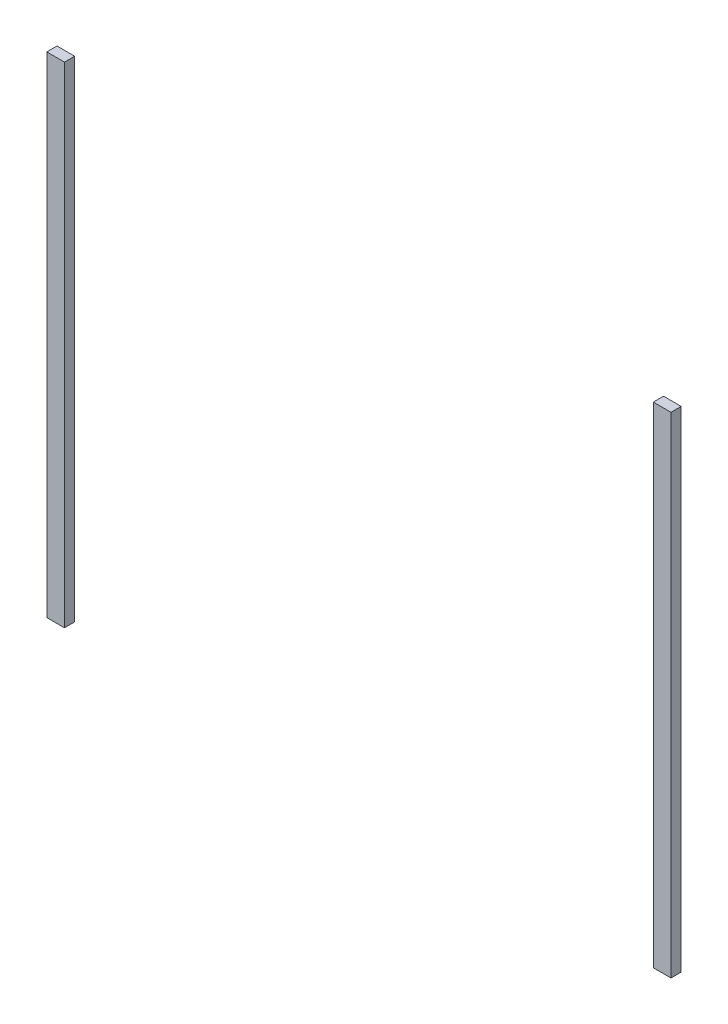
SolidWorks part; units mm, degrees
ref_plane "Front Plane" through (0, 0, 0) normal (0, 0, 1) x (1, 0, 0)
ref_plane "Top Plane" through (0, 0, 0) normal (0, 1, 0) x (1, 0, 0)
ref_plane "Right Plane" through (0, 0, 0) normal (1, 0, 0) x (0, 0, -1)
sketch "Sketch1" plane through (0, 609.6, 0) normal (0, 1, 0) x (1, 0, 0)
  line L4 (366.3353, -647.2114) -> (366.3353, -659.9114)
  line L5 (388.3323, -647.2114) -> (366.3353, -647.2114)
  line L6 (388.3323, -659.9114) -> (388.3323, -647.2114)
  line L7 (366.3353, -659.9114) -> (388.3323, -659.9114)
  line L8 (366.3353, -647.2114) -> (366.3353, -659.9114)
  line L9 (388.3323, -647.2114) -> (366.3353, -647.2114)
  line L10 (388.3323, -659.9114) -> (388.3323, -647.2114)
  line L11 (366.3353, -659.9114) -> (388.3323, -659.9114)
  line L12 (-366.3353, -659.9114) -> (-366.3353, -647.2114)
  line L13 (-366.3353, -647.2114) -> (-388.3323, -647.2114)
  line L14 (-388.3323, -647.2114) -> (-388.3323, -659.9114)
  line L15 (-388.3323, -659.9114) -> (-366.3353, -659.9114)
  line L16 (-366.3353, -659.9114) -> (-366.3353, -647.2114)
  line L17 (-366.3353, -647.2114) -> (-388.3323, -647.2114)
  line L18 (-388.3323, -647.2114) -> (-388.3323, -659.9114)
  line L19 (-388.3323, -659.9114) -> (-366.3353, -659.9114)
  dimension "D1" = 0
  dimension "D2" = 0
extrude "Boss-Extrude1" add sketch "Sketch1" against normal up to vertex (609.6 mm away)
